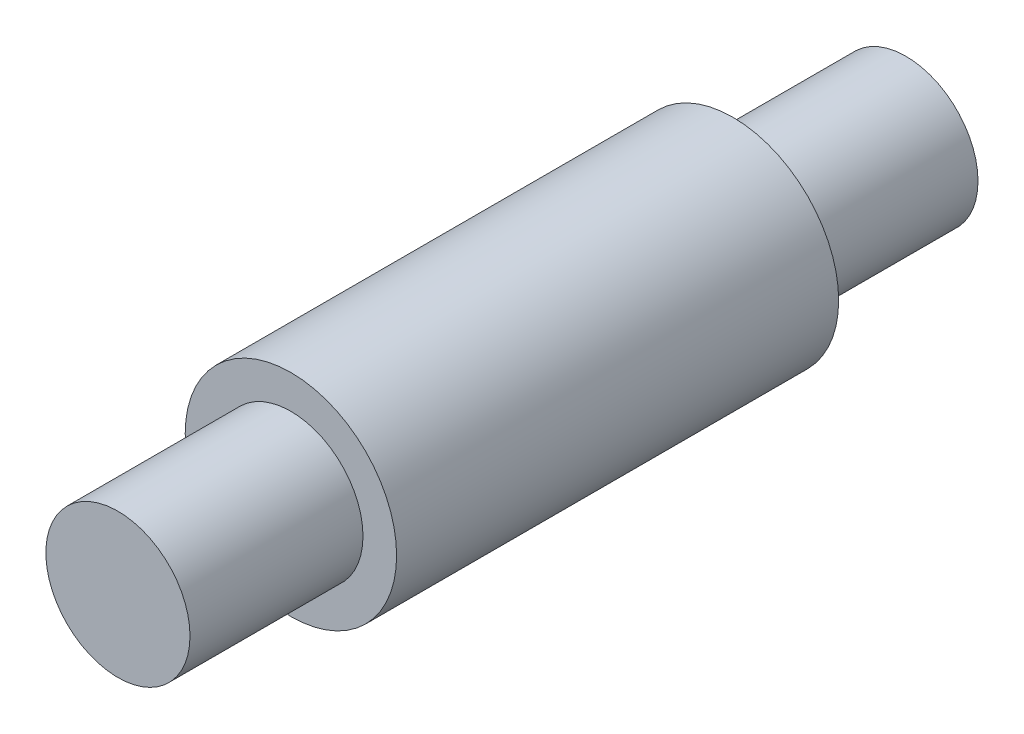
SolidWorks part; units mm, degrees
material "AISI 1020"
ref_plane "Front Plane" through (0, 0, 0) normal (0, 0, 1) x (1, 0, 0)
ref_plane "Top Plane" through (0, 0, 0) normal (0, 1, 0) x (1, 0, 0)
ref_plane "Right Plane" through (0, 0, 0) normal (1, 0, 0) x (0, 0, -1)
sketch "Sketch1" plane through (0, 0, 0) normal (0, 0, 1) x (1, 0, 0)
  circle A0 centre (0, 0) radius 11
  dimension "D1" = 22
extrude "Boss-Extrude1" add sketch "Sketch1" along normal mid plane 46
sketch "Sketch2" plane through (0, 0, 23) normal (0, 0, 1) x (1, 0, 0)
  circle A0 centre (0, 0) radius 7.5
  dimension "D1" = 15
extrude "Boss-Extrude2" add sketch "Sketch2" along normal blind 18
cosmetic thread "Cosmetic Thread1" parameters "D1"=13, "D2"=11.797
mirror "Mirror1" about plane through (0, 0, 0) normal (0, 0, 1) of "Boss-Extrude2"
cosmetic thread "Cosmetic Thread2" parameters "D1"=13, "D2"=11.797
cosmetic thread "Cosmetic Thread3" parameters "D1"=13, "D2"=11.797
